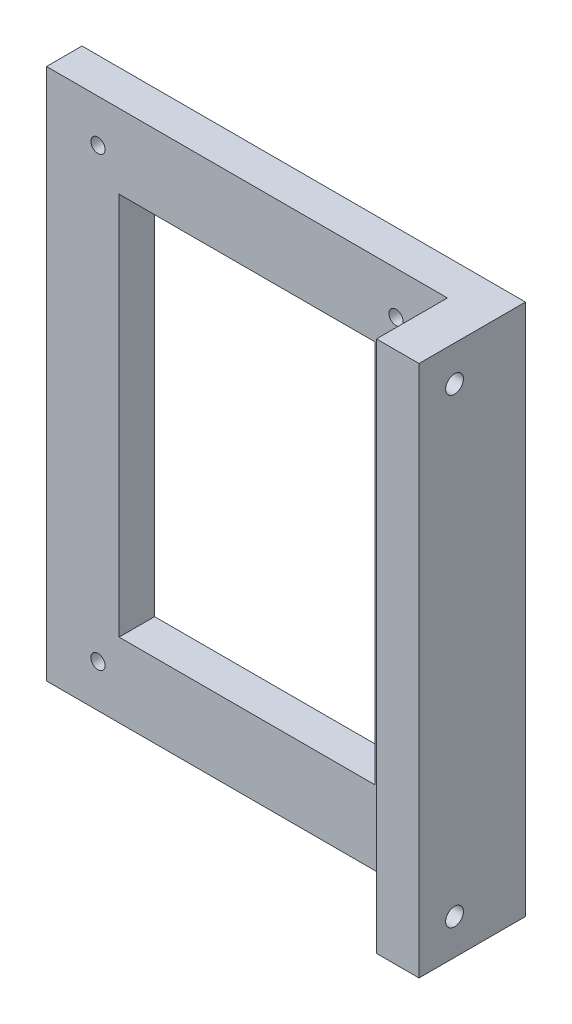
SolidWorks part; units mm, degrees
ref_plane "前视基准面" through (0, 0, 0) normal (0, 0, 1) x (1, 0, 0)
ref_plane "上视基准面" through (0, 0, 0) normal (0, 1, 0) x (1, 0, 0)
ref_plane "右视基准面" through (0, 0, 0) normal (1, 0, 0) x (0, 0, -1)
sketch "草图1" plane through (0, 0, 0) normal (0, 0, 1) x (1, 0, 0)
  line L0 (-19.6154, -26.8077) -> (93.3846, -26.8077) construction
  line L1 (-19.6154, 48.1923) -> (93.3846, 48.1923)
  line L2 (-19.6154, 48.1923) -> (-19.6154, -101.8077)
  line L3 (-19.6154, -101.8077) -> (93.3846, -101.8077)
  line L4 (93.3846, 48.1923) -> (93.3846, -101.8077)
  line L10 (-5.1154, 36.1923) -> (78.8846, -89.8077) construction
  line L11 (-5.1154, -89.8077) -> (78.8846, 36.1923) construction
  line L12 (0.8426, 27.2553) -> (72.9266, 27.2553)
  line L13 (0.8426, 27.2553) -> (0.8426, -80.8707)
  line L14 (0.8426, -80.8707) -> (72.9266, -80.8707)
  line L15 (72.9266, 27.2553) -> (72.9266, -80.8707)
  line L16 (0.8426, 27.2553) -> (72.9266, -80.8707) construction
  line L17 (0.8426, -80.8707) -> (72.9266, 27.2553) construction
  circle A0 centre (78.8846, 36.1923) radius 2
  circle A1 centre (-5.1154, 36.1923) radius 2
  circle A2 centre (78.8846, -89.8077) radius 2
  circle A3 centre (-5.1154, -89.8077) radius 2
  point P6 (36.8846, -26.8077)
  point P15 (36.8846, -26.8077)
  dimension "D1" = 113
  dimension "D2" = 150
  dimension "D3" = 84
  dimension "D4" = 126
extrude "凸台-拉伸1" add sketch "草图1" along normal blind 10
sketch "草图2" plane through (93.3846, 0, 0) normal (1, 0, 0) x (0, 0, -1)
  line L1 (0, 48.1923) -> (-30, 48.1923)
  line L2 (0, 48.1923) -> (0, -101.8077)
  line L3 (0, -101.8077) -> (-30, -101.8077)
  line L4 (-30, 48.1923) -> (-30, -101.8077)
  dimension "D1" = 150
  dimension "D2" = 30
extrude "凸台-拉伸2" add sketch "草图2" along normal blind 12
sketch "草图3" plane through (93.3846, 0, 0) normal (-1, 0, 0) x (0, 0, 1)
  line L0 (30, 48.1923) -> (10, 48.1923) construction
  line L1 (20, 48.1923) -> (20, 38.1923) construction
  line L2 (30, -26.8077) -> (10, -26.8077) construction
  line L3 (30, 48.1923) -> (30, -101.8077) construction
  line L4 (10, -101.8077) -> (10, 48.1923) construction
  circle A0 centre (20, 38.1923) radius 2.5
  circle A1 centre (20, -91.8077) radius 2.5
  dimension "D1" = 10
extrude "切除-拉伸2" cut sketch "草图3" against normal blind 12
sketch "草图6" plane through (93.3846, 0, 0) normal (-1, 0, 0) x (0, 0, 1)
  line L0 (17.5, 38.1923) -> (22.5, 38.1923) construction
  line L1 (30, -26.8077) -> (10, -26.8077) construction
  line L2 (30, 48.1923) -> (30, -101.8077) construction
  line L3 (10, -101.8077) -> (10, 48.1923) construction
  circle A0 centre (20, 38.1923) radius 2.5 construction
  circle A1 centre (20, 38.1923) radius 4.5
  circle A2 centre (20, -91.8077) radius 4.5
extrude "切除-拉伸5" cut sketch "草图6" against normal blind 5
